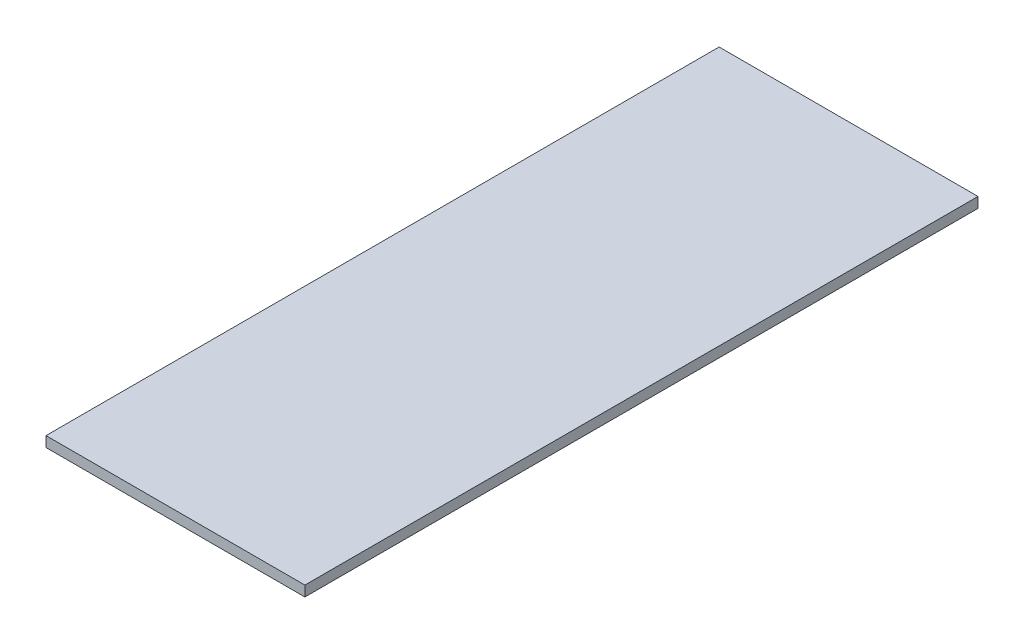
SolidWorks part; units mm, degrees
ref_plane "Front Plane" through (0, 0, 0) normal (0, 0, 1) x (1, 0, 0)
ref_plane "Top Plane" through (0, 0, 0) normal (0, 1, 0) x (1, 0, 0)
ref_plane "Right Plane" through (0, 0, 0) normal (1, 0, 0) x (0, 0, -1)
sketch "Sketch1" plane through (0, 0, 0) normal (0, 1, 0) x (1, 0, 0)
  line L1 (-60.119, 244.2559) -> (66.881, 244.2559)
  line L2 (-60.119, 244.2559) -> (-60.119, -85.9441)
  line L3 (-60.119, -85.9441) -> (66.881, -85.9441)
  line L4 (66.881, 244.2559) -> (66.881, -85.9441)
  dimension "D1" = 330.2
extrude "Boss-Extrude1" add sketch "Sketch1" along normal blind 5.08
